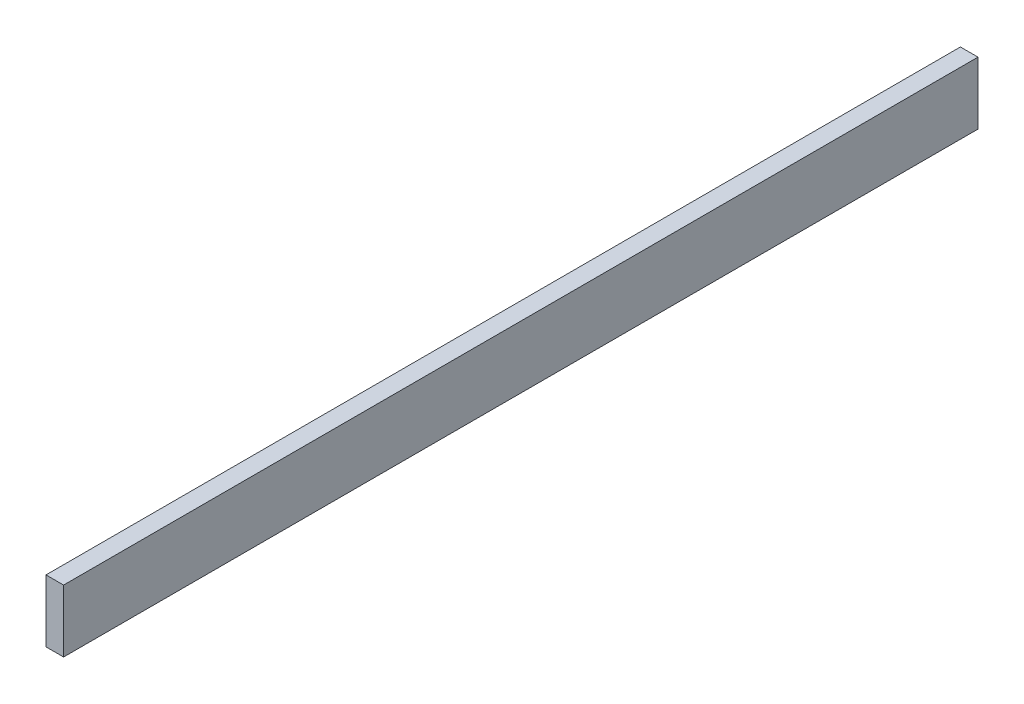
SolidWorks part; units mm, degrees
ref_plane "Front Plane" through (0, 0, 0) normal (0, 0, 1) x (1, 0, 0)
ref_plane "Top Plane" through (0, 0, 0) normal (0, 1, 0) x (1, 0, 0)
ref_plane "Right Plane" through (0, 0, 0) normal (1, 0, 0) x (0, 0, -1)
other "Configuration Table"
sketch "Sketch1" plane through (0, 0, 0) normal (0, 0, 1) x (1, 0, 0)
  line L1 (605.3, 14) -> (618, 14)
  line L2 (605.3, 14) -> (605.3, 59)
  line L3 (605.3, 59) -> (618, 59)
  line L4 (618, 14) -> (618, 59)
extrude "CEK_1L_ray_ic_profil_sag_1" add sketch "Sketch1" against normal blind 660 separate body
